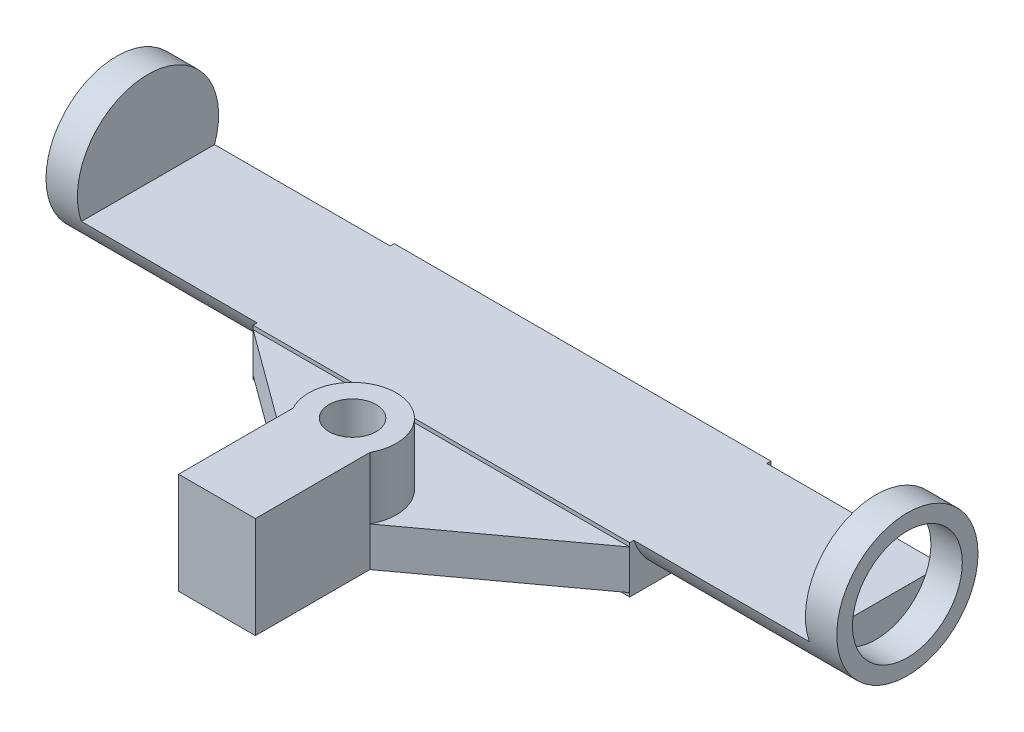
SolidWorks part; units mm, degrees
ref_plane "Front Plane" through (0, 0, 0) normal (0, 0, 1) x (1, 0, 0)
ref_plane "Top Plane" through (0, 0, 0) normal (0, 1, 0) x (1, 0, 0)
ref_plane "Right Plane" through (0, 0, 0) normal (1, 0, 0) x (0, 0, -1)
sketch "Sketch1" plane through (0, 0, 0) normal (0, 1, 0) x (1, 0, 0)
  line L1 (59.2176, -23.8423) -> (-100.7824, -23.8423)
  line L2 (59.2176, -23.8423) -> (59.2176, 4.7327)
  line L3 (59.2176, 4.7327) -> (-100.7824, 4.7327)
  line L4 (-100.7824, -23.8423) -> (-100.7824, 4.7327)
  dimension "D1" = 28.575
  dimension "D2" = 160
extrude "Boss-Extrude1" add sketch "Sketch1" along normal blind 28.575
sketch "Sketch2" plane through (59.2176, 0, 0) normal (1, 0, 0) x (0, 0, -1)
  line L0 (-9.5548, 28.575) -> (-9.5548, 0) construction
  line L1 (-23.8423, 28.575) -> (4.7327, 28.575) construction
  line L2 (-23.8423, 0) -> (4.7327, 0) construction
  line L3 (4.7327, 14.2875) -> (-23.8423, 14.2875) construction
  line L4 (4.7327, 28.575) -> (4.7327, 0) construction
  line L5 (-23.8423, 28.575) -> (-23.8423, 0) construction
  circle A0 centre (-9.5548, 14.2875) radius 14.2875
sketch "Sketch3" plane through (0, 28.575, 0) normal (0, 1, 0) x (1, 0, 0)
  line L0 (59.2176, 4.7327) -> (-100.7824, 4.7327) construction
  line L1 (-94.4324, 4.7327) -> (52.8676, 4.7327)
  line L2 (-94.4324, 4.7327) -> (-94.4324, -23.8423)
  line L3 (-94.4324, -23.8423) -> (52.8676, -23.8423)
  line L4 (52.8676, 4.7327) -> (52.8676, -23.8423)
  line L5 (-100.7824, -23.8423) -> (59.2176, -23.8423) construction
  line L6 (-100.7824, 4.7327) -> (-100.7824, -23.8423) construction
  dimension "D1" = 147.3
  dimension "D2" = 6.35
extrude "Cut-Extrude3" cut sketch "Sketch3" against normal blind 19.05
sketch "Sketch4" plane through (0, 0, 23.8423) normal (0, 0, 1) x (1, 0, 0)
  line L0 (-20.7824, 9.525) -> (-20.7824, 0) construction
  line L1 (-94.4324, 9.525) -> (52.8676, 9.525) construction
  line L2 (-100.7824, 0) -> (59.2176, 0) construction
  line L4 (17.3176, 0.7625) -> (-58.8824, 0.7625)
  line L5 (17.3176, 0.7625) -> (17.3176, 8.7625)
  line L6 (17.3176, 8.7625) -> (-58.8824, 8.7625)
  line L7 (-58.8824, 0.7625) -> (-58.8824, 8.7625)
  line L8 (17.3176, 0.7625) -> (-58.8824, 8.7625) construction
  line L9 (17.3176, 8.7625) -> (-58.8824, 0.7625) construction
  point P6 (-20.7824, 4.7625)
  dimension "D1" = 76.2
  dimension "D2" = 8
extrude "Boss-Extrude2" add sketch "Sketch4" along normal blind 45.4
sketch "Sketch5" plane through (0, 8.7625, 0) normal (0, 1, 0) x (1, 0, 0)
  line L0 (-20.7824, -23.8423) -> (-20.7824, -69.2423) construction
  line L1 (-94.4324, -23.8423) -> (52.8676, -23.8423) construction
  line L2 (17.3176, -69.2423) -> (-58.8824, -69.2423) construction
  line L3 (17.3176, -38.1298) -> (-58.8824, -38.1298) construction
  line L4 (-28.5508, -46.0758) -> (-28.5508, -69.2423)
  line L5 (-28.5508, -69.2423) -> (-28.5508, -46.0758)
  line L6 (-13.0139, -46.0758) -> (-13.0139, -69.2423)
  line L7 (17.3176, -69.2423) -> (17.3176, -23.8423) construction
  line L8 (-58.8824, -69.2423) -> (-58.8824, -23.8423) construction
  line L9 (17.3176, -23.8423) -> (-58.8824, -23.8423) construction
  line L10 (-58.8824, -23.8423) -> (-28.5508, -46.0758)
  line L11 (17.3176, -23.8423) -> (-13.0139, -46.0758)
  line L12 (17.3176, -23.8423) -> (17.3176, -69.2423)
  line L13 (17.3176, -69.2423) -> (-13.0139, -69.2423)
  line L14 (-28.5508, -69.2423) -> (-58.8824, -69.2423)
  line L15 (-58.8824, -69.2423) -> (-58.8824, -23.8423)
  line M2 (-58.8824, -23.8423) -> (-58.8824, -69.2423)
  line M3 (-58.8824, -69.2423) -> (17.3176, -69.2423)
  line M4 (17.3176, -69.2423) -> (17.3176, -23.8423)
  dimension "D1" = 14.2875
extrude "Cut-Extrude8" cut sketch "Sketch5" against normal through all contours L11 L6 M4 M3 | L10 L4 M2 M3
sketch "Sketch9" plane through (0, 8.7625, 0) normal (0, 1, 0) x (1, 0, 0)
  line L0 (-46.4509, -32.9548) -> (4.8861, -32.9548) construction
  line L1 (-58.8824, -23.8423) -> (-28.5508, -46.0758) construction
  line L2 (17.3176, -23.8423) -> (-13.0139, -46.0758) construction
  line L3 (17.3176, -23.8423) -> (-58.8824, -23.8423) construction
  line L4 (-28.5508, -46.0758) -> (-28.5508, -69.2423)
  line L5 (-28.5508, -69.2423) -> (-13.0139, -69.2423)
  line L6 (-13.0139, -69.2423) -> (-13.0139, -46.0758)
  arc A0 (-13.0139, -46.0758) -> (-28.5508, -46.0758) centre (-20.7824, -41.815) ccw
  circle A2 centre (-20.7824, -41.815) radius 4.7625
  dimension "D1" = 9.1125
extrude "Boss-Extrude4" add sketch "Sketch9" along normal blind 12.525
sketch "Sketch10" plane through (0, 8.7625, 0) normal (0, 1, 0) x (1, 0, 0)
  circle A0 centre (-20.7824, -41.815) radius 4.7625
extrude "Cut-Extrude10" cut sketch "Sketch10" against normal through all
extrude "Cut-Extrude11" cut sketch "Sketch2" against normal up to vertex flip side to cut
sketch "Sketch13" plane through (-100.7824, 0, 0) normal (-1, 0, 0) x (0, 0, 1)
  line L0 (9.5548, 28.575) -> (9.5548, 0) construction
  line L1 (-4.7327, 28.575) -> (23.8423, 28.575) construction
  line L2 (-4.7327, 0) -> (23.8423, 0) construction
  line L3 (23.8423, 14.2875) -> (-4.7327, 14.2875) construction
  line L4 (23.8423, 28.575) -> (23.8423, 0) construction
  line L5 (-4.7327, 28.575) -> (-4.7327, 0) construction
  circle A0 centre (9.5548, 14.2875) radius 14.2875
  dimension "D1" = 28.575
extrude "Cut-Extrude13" cut sketch "Sketch13" against normal up to vertex flip side to cut
sketch "Sketch14" plane through (59.2176, 0, 0) normal (1, 0, 0) x (0, 0, -1)
  line L0 (-9.5548, 0) -> (-9.5548, 28.575) construction
  circle A0 centre (-9.5548, 14.2875) radius 14.2875 construction
  circle A1 centre (-9.5548, 14.2875) radius 11.1125
extrude "Cut-Extrude14" cut sketch "Sketch14" against normal up to surface (6.35 mm away) up to face at (52.8676, 19.05, 9.5548)
